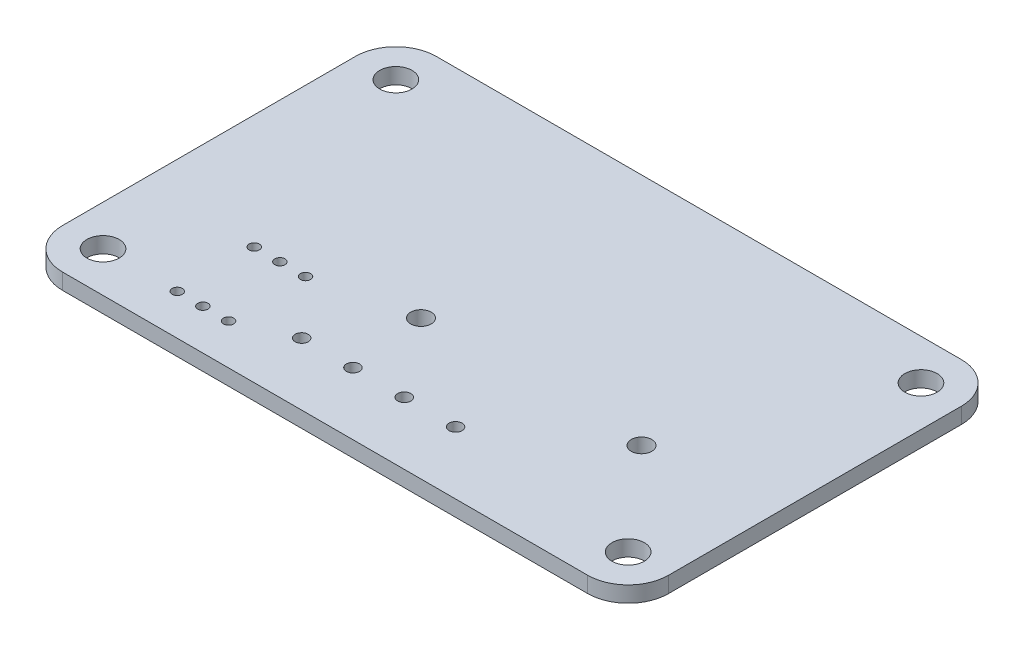
SolidWorks part; units mm, degrees
ref_plane "Front Plane" through (0, 0, 0) normal (0, 0, 1) x (1, 0, 0)
ref_plane "Top Plane" through (0, 0, 0) normal (0, 1, 0) x (1, 0, 0)
ref_plane "Right Plane" through (0, 0, 0) normal (1, 0, 0) x (0, 0, -1)
sketch "Sketch1" plane through (0, 0, 0) normal (0, 1, 0) x (1, 0, 0)
  line L1 (-30, -18.5) -> (30, -18.5)
  line L2 (-30, -18.5) -> (-30, 18.5)
  line L3 (-30, 18.5) -> (30, 18.5)
  line L4 (30, -18.5) -> (30, 18.5)
  line L5 (-30, -18.5) -> (30, 18.5) construction
  line L6 (-30, 18.5) -> (30, -18.5) construction
  point P0 (0, 0)
  dimension "D1" = 60
  dimension "D2" = 37
extrude "Boss-Extrude1" add sketch "Sketch1" along normal blind 1.5748
fillet "Fillet1" radius 4 4 edges at (30, 0.7874, 18.5) (30, 0.7874, -18.5) (-30, 0.7874, -18.5) (-30, 0.7874, 18.5)
sketch "Sketch2" plane through (0, 1.5748, 0) normal (0, 1, 0) x (1, 0, 0)
  circle A0 centre (-26, 14.5) radius 1.6
  circle A1 centre (-26, -14.5) radius 1.6
  circle A2 centre (26, -14.5) radius 1.6
  circle A3 centre (26, 14.5) radius 1.6
  dimension "D1" = 3.2
extrude "Cut-Extrude1" cut sketch "Sketch2" against normal through all
sketch "Sketch3" plane through (0, 1.5748, 0) normal (0, 1, 0) x (-1, 0, 0)
  line L0 (4.318, 4.699) -> (-17.526, 4.699) construction
  circle A0 centre (4.318, 4.699) radius 1.016
  circle A1 centre (-17.526, 4.699) radius 1.016
  dimension "D4" = 2.032
  dimension "D1" = 4.318
  dimension "D2" = 4.699
  dimension "D3" = 17.526
extrude "Cut-Extrude2" cut sketch "Sketch3" against normal through all
sketch "Sketch4" plane through (0, 1.5748, 0) normal (0, 1, 0) x (1, 0, 0)
  circle A0 centre (6.731, -12.319) radius 0.6477
  dimension "D3" = 1.2954
  dimension "D1" = 6.731
  dimension "D2" = 12.319
extrude "Cut-Extrude3" cut sketch "Sketch4" against normal through all
pattern_linear "LPattern1" count 4 spacing 5.08 along (-1, 0, 0) of "Cut-Extrude3"
sketch "Sketch5" plane through (0, 1.5748, 0) normal (0, 1, 0) x (1, 0, 0)
  circle A0 centre (-13.589, -14.478) radius 0.508
  dimension "D1" = 1.016
  dimension "D2" = 13.589
  dimension "D3" = 14.478
extrude "Cut-Extrude4" cut sketch "Sketch5" against normal through all
pattern_linear "LPattern2" count 3 spacing 2.54 along (-1, 0, 0) count 2 spacing 7.62 along (0, 0, -1) of "Cut-Extrude4"
